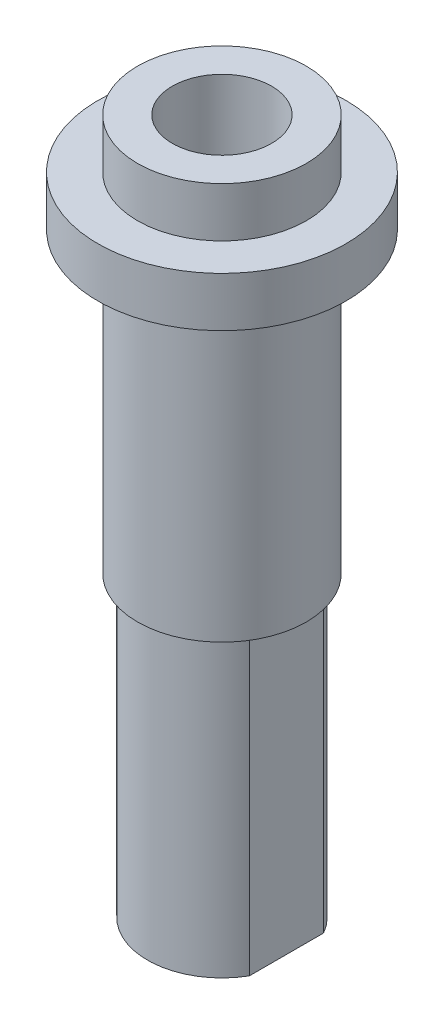
SolidWorks part; units mm, degrees
material "Простая углеродистая сталь"
ref_plane "Спереди" through (0, 0, 0) normal (0, 0, 1) x (1, 0, 0)
ref_plane "Сверху" through (0, 0, 0) normal (0, 1, 0) x (1, 0, 0)
ref_plane "Справа" through (0, 0, 0) normal (1, 0, 0) x (0, 0, -1)
sketch "Эскиз1" plane through (0, 0, 0) normal (0, 0, 1) x (1, 0, 0)
  line L0 (0, 0) -> (0, 49.3836) construction
  line L1 (5, 70) -> (5, 0)
  line L2 (5, 0) -> (8.5, 0)
  line L3 (8.5, 0) -> (8.5, 60)
  line L4 (8.5, 60) -> (12.5, 60)
  line L5 (12.5, 60) -> (12.5, 65)
  line L6 (12.5, 65) -> (8.5, 65)
  line L7 (8.5, 65) -> (8.5, 70)
  line L8 (8.5, 70) -> (5, 70)
  dimension "D1" = 10
  dimension "D2" = 17
  dimension "D3" = 60
  dimension "D4" = 5
  dimension "D5" = 25
  dimension "D6" = 5
revolve "Повернуть1" add sketch "Эскиз1" angle 360 about L0
cosmetic thread "Условное изображение резьбы1" parameters "D2"=12
sketch "Эскиз2" plane through (0, 0, 0) normal (0, -1, 0) x (1, 0, 0)
  line L0 (6.5, 3.7417) -> (6.5, -3.7417)
  arc A0 (6.5, 3.7417) -> (6.5, -3.7417) centre (0, 0) ccw
  dimension "D1" = 6.5
  dimension "D2" = 15
extrude "Вырез-Вытянуть1" cut sketch "Эскиз2" against normal blind 30 flip side to cut
